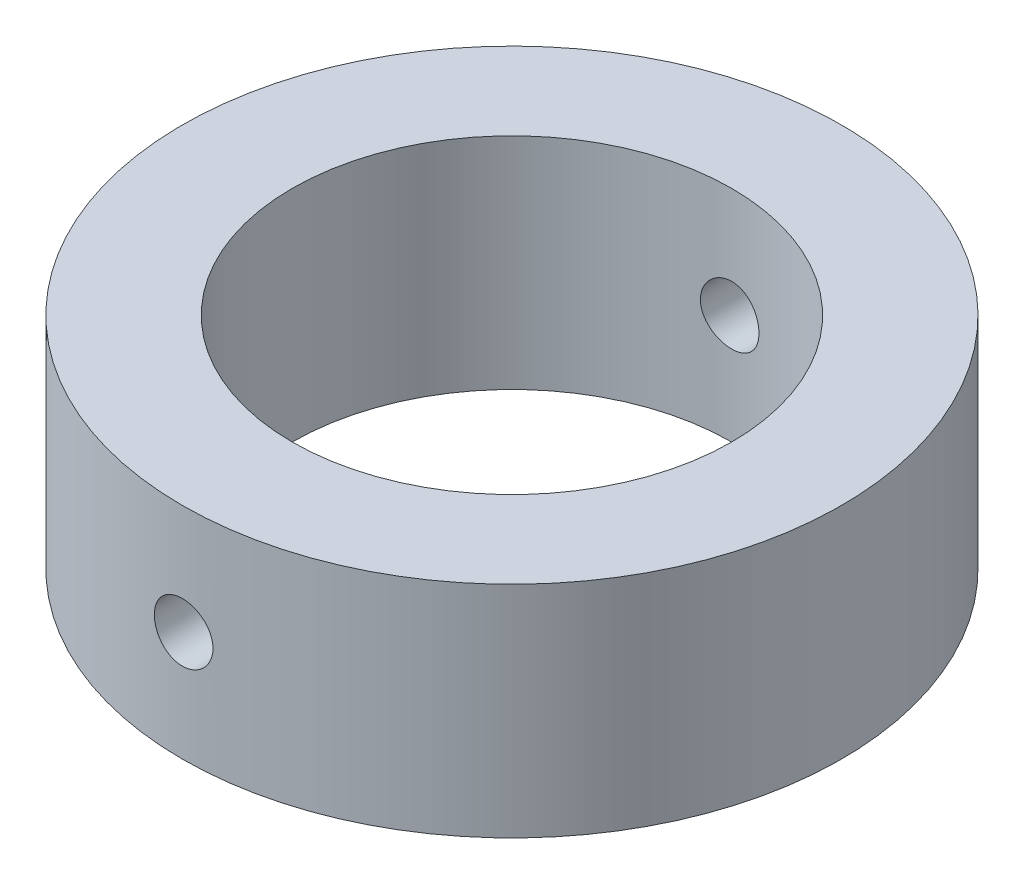
SolidWorks part; units mm, degrees
ref_plane "Front Plane" through (0, 0, 0) normal (0, 0, 1) x (1, 0, 0)
ref_plane "Top Plane" through (0, 0, 0) normal (0, 1, 0) x (1, 0, 0)
ref_plane "Right Plane" through (0, 0, 0) normal (1, 0, 0) x (0, 0, -1)
sketch "Sketch1" plane through (0, 0, 0) normal (0, 1, 0) x (1, 0, 0)
  circle A0 centre (0, 0) radius 22.5
  circle A1 centre (0, 0) radius 15
  dimension "D1" = 30
  dimension "D2" = 45
extrude "Boss-Extrude1" add sketch "Sketch1" along normal blind 15
sketch "Sketch2" plane through (0, 0, 0) normal (0, 0, 1) x (1, 0, 0)
  line L0 (0, 0) -> (0, 15) construction
  line L1 (22.5, 15) -> (-22.5, 15) construction
  circle A0 centre (0, 7.5) radius 2
  point P7 (0, 7.5)
  dimension "D1" = 4
extrude "Cut-Extrude1" cut sketch "Sketch2" against normal through all both and the other way through all
